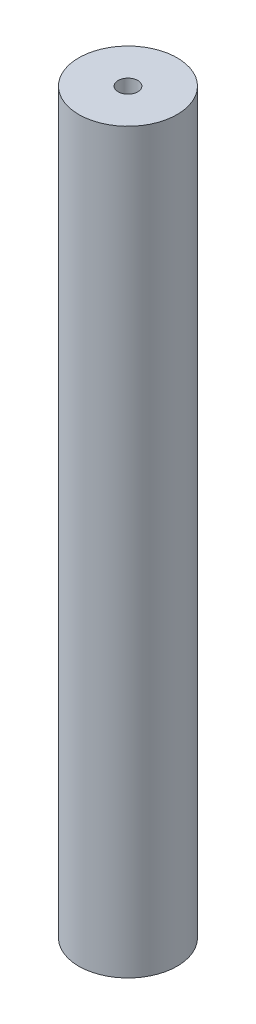
SolidWorks part; units mm, degrees
ref_plane "Front Plane" through (0, 0, 0) normal (0, 0, 1) x (1, 0, 0)
ref_plane "Top Plane" through (0, 0, 0) normal (0, 1, 0) x (1, 0, 0)
ref_plane "Right Plane" through (0, 0, 0) normal (1, 0, 0) x (0, 0, -1)
sketch "Sketch1" plane through (0, 0, 0) normal (0, 1, 0) x (1, 0, 0)
  circle A1 centre (0, 0) radius 20
  circle A2 centre (0, 0) radius 4
  dimension "D1" = 8
  dimension "D2" = 40
extrude "Boss-Extrude1" add sketch "Sketch1" along normal blind 300
